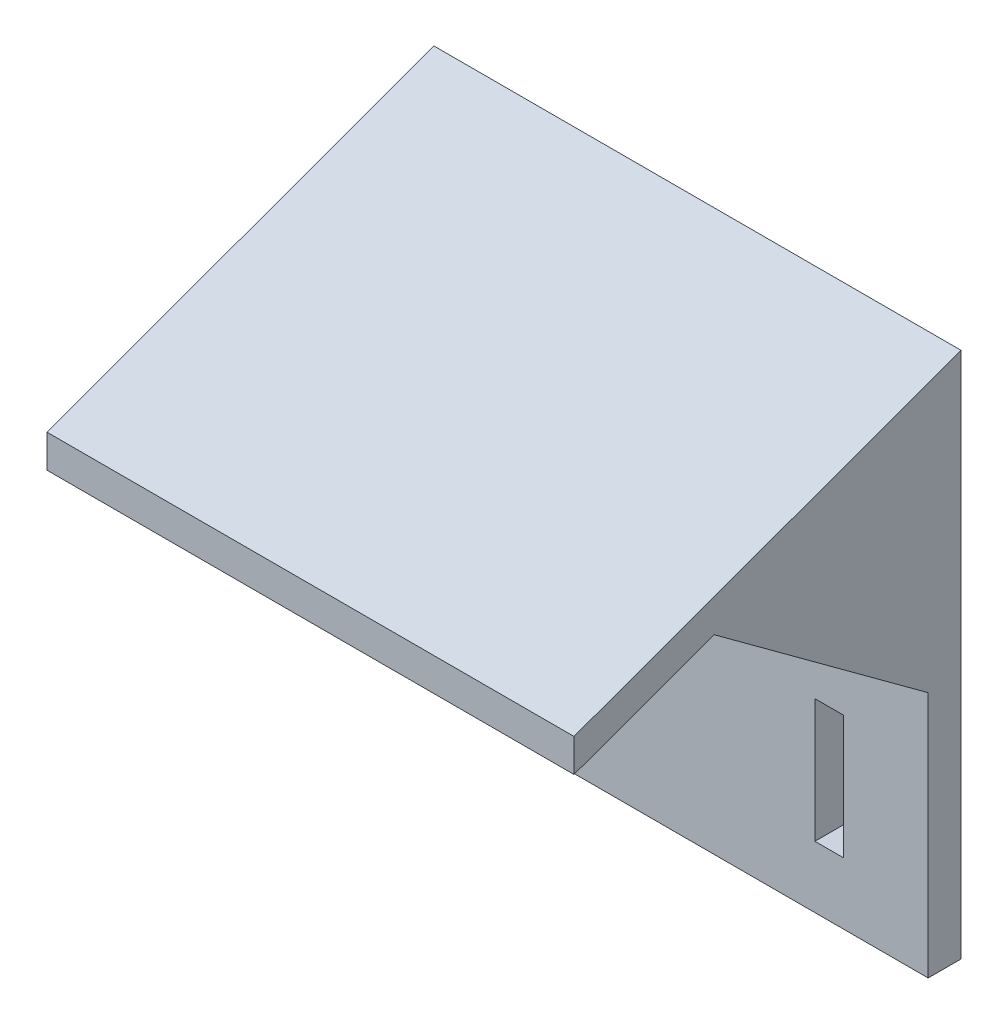
SolidWorks part; units mm, degrees
material "ABS"
ref_plane "Front Plane" through (0, 0, 0) normal (0, 0, 1) x (1, 0, 0)
ref_plane "Top Plane" through (0, 0, 0) normal (0, 1, 0) x (1, 0, 0)
ref_plane "Right Plane" through (0, 0, 0) normal (1, 0, 0) x (0, 0, -1)
sketch "Sketch1" plane through (0, 0, 0) normal (1, 0, 0) x (0, 0, -1)
  line L0 (0, 0) -> (-4, 0)
  line L1 (-4, 0) -> (-4, 30)
  line L2 (-4, 30) -> (-30, 49.1)
  line L3 (-30, 49.1) -> (-47, 42.9)
  line L4 (-47, 42.9) -> (-47, 46.9)
  line L5 (-47, 46.9) -> (0, 64)
  line L6 (0, 64) -> (0, 0)
extrude "Boss-Extrude1" add sketch "Sketch1" along normal mid plane 64
sketch "Sketch2" plane through (0, 0, 0) normal (0, 0, -1) x (-1, 0, 0)
  line L1 (18.25, 7.5) -> (21.75, 7.5)
  line L2 (18.25, 7.5) -> (18.25, 22.5)
  line L3 (18.25, 22.5) -> (21.75, 22.5)
  line L4 (21.75, 7.5) -> (21.75, 22.5)
  line L5 (18.25, 7.5) -> (21.75, 22.5) construction
  line L6 (18.25, 22.5) -> (21.75, 7.5) construction
  line L7 (-21.75, 7.5) -> (-18.25, 7.5)
  line L8 (-21.75, 7.5) -> (-21.75, 22.5)
  line L9 (-21.75, 22.5) -> (-18.25, 22.5)
  line L10 (-18.25, 7.5) -> (-18.25, 22.5)
  line L11 (-21.75, 7.5) -> (-18.25, 22.5) construction
  line L12 (-21.75, 22.5) -> (-18.25, 7.5) construction
  point P0 (20, 15)
  point P5 (-20, 15)
extrude "Cut-Extrude1" cut sketch "Sketch2" against normal through all
